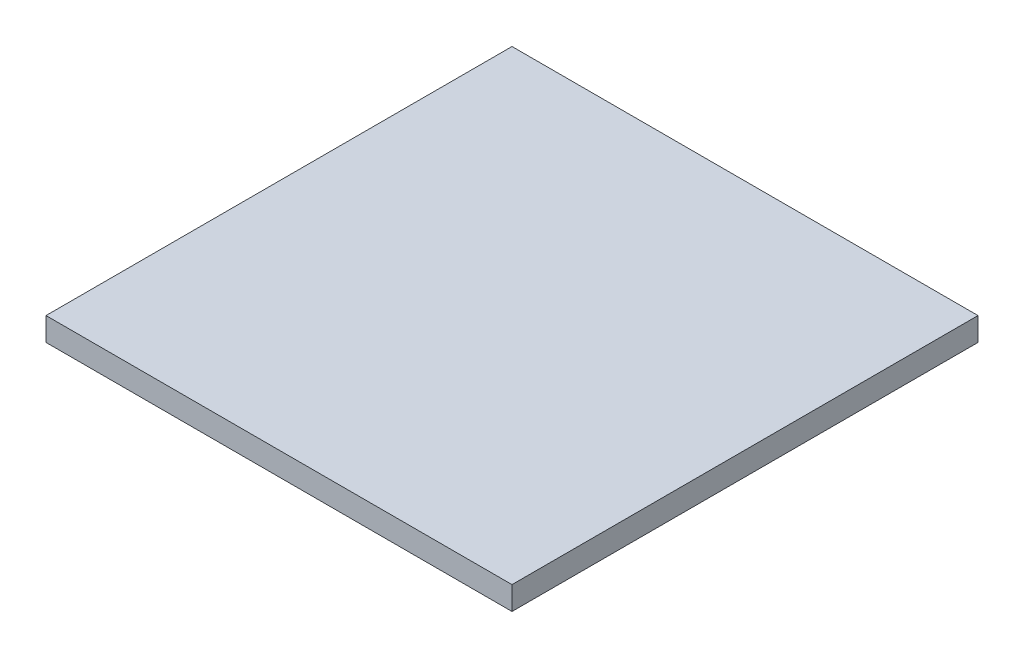
SolidWorks part; units mm, degrees
material "ABS"
ref_plane "Front Plane" through (0, 0, 0) normal (0, 0, 1) x (1, 0, 0)
ref_plane "Top Plane" through (0, 0, 0) normal (0, 1, 0) x (1, 0, 0)
ref_plane "Right Plane" through (0, 0, 0) normal (1, 0, 0) x (0, 0, -1)
sketch "Sketch1" plane through (0, 0, 0) normal (0, 1, 0) x (1, 0, 0)
  line L1 (-50, 50) -> (50, 50)
  line L2 (-50, 50) -> (-50, -50)
  line L3 (-50, -50) -> (50, -50)
  line L4 (50, 50) -> (50, -50)
  line L5 (-50, 50) -> (50, -50) construction
  line L6 (-50, -50) -> (50, 50) construction
  point P0 (0, 0)
extrude "Boss-Extrude1" add sketch "Sketch1" along normal mid plane 5
